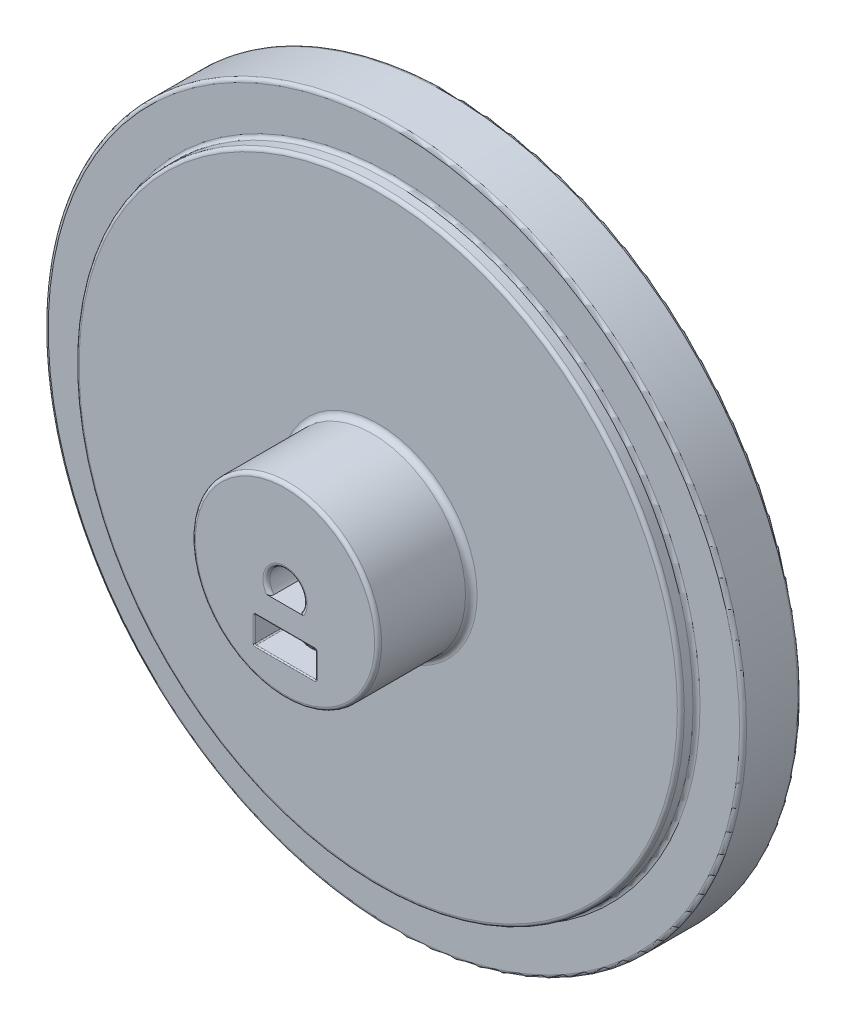
SolidWorks part; units mm, degrees
ref_plane "Front Plane" through (0, 0, 0) normal (0, 0, 1) x (1, 0, 0)
ref_plane "Top Plane" through (0, 0, 0) normal (0, 1, 0) x (1, 0, 0)
ref_plane "Right Plane" through (0, 0, 0) normal (1, 0, 0) x (0, 0, -1)
sketch "Sketch1" plane through (0, 0, 0) normal (0, 0, 1) x (1, 0, 0)
  circle A0 centre (0, 0) radius 30
  dimension "D1" = 60
extrude "Boss-Extrude1" add sketch "Sketch1" along normal mid plane 7.7
sketch "Sketch2" plane through (0, 0, 0) normal (0, 1, 0) x (1, 0, 0)
  line L1 (25, 0) -> (23.8588, 0) construction
  line L2 (30, -3.85) -> (30, 3.85) construction
  line L3 (26, 2.5) -> (36.8772, 2.5)
  line L4 (36.8772, 2.5) -> (36.8772, -2.5)
  line L5 (26, 2.5) -> (26, 7.2558)
  line L6 (26, 7.2558) -> (39.5043, 7.2558)
  line L7 (39.5043, 7.2558) -> (39.5043, -7.2558)
  line L8 (26, -7.2558) -> (39.5043, -7.2558)
  line L9 (26, -2.5) -> (26, -7.2558)
  line L10 (26, -2.5) -> (36.8772, -2.5)
  point P10 (39.5043, 0)
  point P13 (36.8772, 0)
  dimension "D1" = 5
  dimension "D2" = 4
sweep "Cut-Sweep1" cut profiles "Sketch2" path edge at (30, 0, -3.85)
sketch "Sketch3" plane through (0, 0, 0) normal (0, 1, 0) x (1, 0, 0)
  line L0 (-27.5, 0) -> (27.5, 0) construction
  line L1 (28.85, 0) -> (28.85, -1.1107) construction
  circle A0 centre (26.25, 0) radius 2.6
  dimension "D2" = 5.2
  dimension "D1" = 28.85
sketch "Sketch4" plane through (0, 0, 3.85) normal (0, 0, 1) x (1, 0, 0)
  circle A0 centre (0, 0) radius 8
  dimension "D1" = 16
extrude "Boss-Extrude2" add sketch "Sketch4" along normal blind 8
sketch "Sketch5" plane through (0, 0, 11.85) normal (0, 0, 1) x (1, 0, 0)
  line L1 (-1.249, -1) -> (1.249, -1)
  arc A0 (1.249, -1) -> (-1.249, -1) centre (0, 0) ccw
  dimension "D1" = 3.2
  dimension "D2" = 1
extrude "Cut-Extrude1" cut sketch "Sketch5" against normal blind 9
sketch "Sketch6" plane through (0, 0, 0) normal (0, 1, 0) x (1, 0, 0)
  line L0 (0, -4.235) -> (0, 4.235) construction
  line L1 (-8, -11.85) -> (8, -11.85) construction
  circle A0 centre (0, -7.55) radius 2
  dimension "D1" = 4
  dimension "D2" = 4.3
extrude "Cut-Extrude2" cut sketch "Sketch6" against normal through all
fillet "Fillet1" radius 0.5 1 edges at (8, 0, 3.85)
sketch "Sketch7" plane through (0, 0, -3.85) normal (0, 0, -1) x (-1, 0, 0)
  circle A0 centre (0, 0) radius 31.3112
  dimension "D1" = 62.6225
fillet "Fillet2" radius 0.3 1 edges at (8, 0, 11.85)
fillet "Fillet3" radius 0.3 1 edges at (-0.3912, -7.9904, 5.5886)
fillet "Fillet4" radius 0.3 1 edges at (0, 1.6, 11.85)
fillet "Fillet5" radius 0.3 6 edges at (-30, 0, 2.5) (26, 0, -3.85) (26, 0, -2.5) (26, 0, 3.85) (26, 0, 2.5) (30, 0, -2.5)
sketch "Sketch8" plane through (0, 0, 11.85) normal (0, 0, 1) x (1, 0, 0)
  line L1 (-2.65, -3) -> (2.65, -3)
  line L2 (-2.65, -3) -> (-2.65, -5.3)
  line L3 (-2.65, -5.3) -> (2.65, -5.3)
  line L4 (2.65, -3) -> (2.65, -5.3)
  point P4 (0, -3)
  dimension "D1" = 2.3
  dimension "D2" = 5.3
  dimension "D3" = 3
extrude "Cut-Extrude3" cut sketch "Sketch8" against normal blind 9
fillet "Fillet6" radius 0.1 14 edges at (0, -3, 9.55) (0, -3, 11.85) (0, -5.3, 5.55) (0, -5.3, 11.85) (-2.65, -3, 7.35) (-2.65, -5.3, 7.35) (-2.65, -4.15, 11.85) (2.65, -5.3, 7.35) (2.65, -3, 7.35) (2.65, -4.15, 11.85) (0, -3, 2.85) (2.65, -4.15, 2.85) (0, -5.3, 2.85) (-2.65, -4.15, 2.85)
